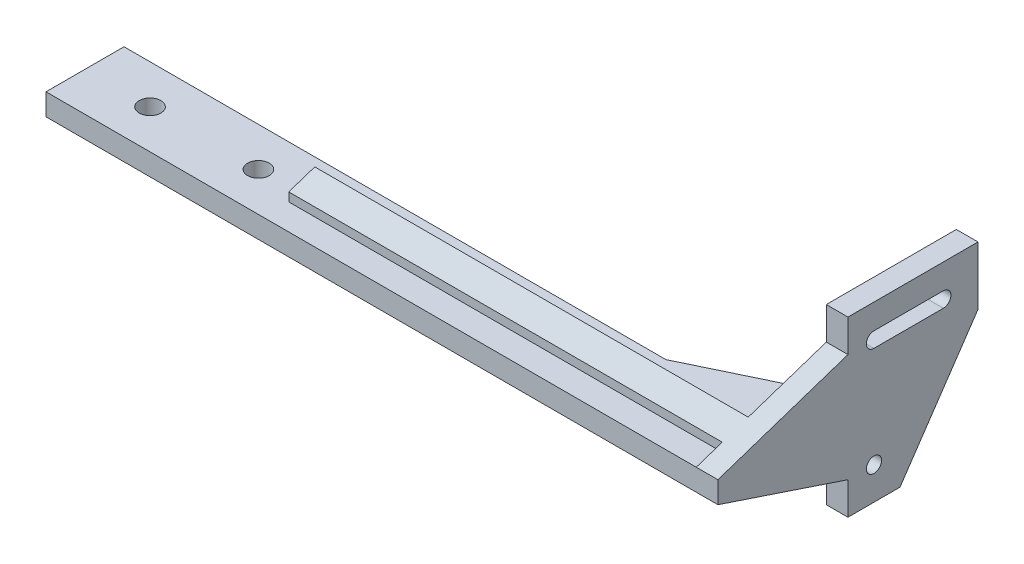
SolidWorks part; units mm, degrees
ref_plane "前视基准面" through (0, 0, 0) normal (0, 0, 1) x (1, 0, 0)
ref_plane "上视基准面" through (0, 0, 0) normal (0, 1, 0) x (1, 0, 0)
ref_plane "右视基准面" through (0, 0, 0) normal (1, 0, 0) x (0, 0, -1)
sketch "草图1" plane through (0, 0, 0) normal (0, 1, 0) x (1, 0, 0)
  line L6 (0, 0) -> (0, -18)
  line L8 (0, -18) -> (150, -18)
  line L9 (150, -18) -> (150, 0)
  line L10 (150, 0) -> (0, 0)
  dimension "D1" = 18
  dimension "D2" = 150
extrude "凸台-拉伸1" add sketch "草图1" along normal blind 5
sketch "草图2" plane through (0, 5, 0) normal (0, 1, 0) x (1, 0, 0)
  line L0 (15, -9) -> (0, -9) construction
  line L1 (0, 0) -> (0, -18) construction
  circle A0 centre (15, -9) radius 2.5
  circle A1 centre (40, -9) radius 2.5
  dimension "D2" = 5
  dimension "D1" = 25
  dimension "D3" = 15
extrude "切除-拉伸1" cut sketch "草图2" against normal through all
sketch "草图6" plane through (150, 0, 0) normal (1, 0, 0) x (0, 0, -1)
  line L0 (12, 15) -> (12, 22.5)
  line L1 (12, 22.5) -> (24, 22.5)
  line L3 (-18, 0) -> (12, -10)
  line L4 (-18, 5) -> (12, 15)
  line L5 (-18, 5) -> (-18, 0)
  line L6 (24, 2.5) -> (-18, 2.5) construction
  line L8 (24, -17.5) -> (42, 9.0298)
  line L9 (24, -17.5) -> (12, -17.5)
  line L10 (12, -17.5) -> (12, -10)
  line L11 (42, 9.0298) -> (42, 22.5)
  line L12 (24, 22.5) -> (42, 22.5)
  point P2 (12, 18.75)
  dimension "D1" = 40
  dimension "D2" = 12
  dimension "D3" = 25
  dimension "D4" = 30
  dimension "D5" = 30
extrude "凸台-拉伸3" add sketch "草图6" along normal blind 5
sketch "草图8" plane through (155, 0, 0) normal (1, 0, 0) x (0, 0, -1)
  line L0 (18, 15) -> (18, -10) construction
  line L1 (18, 2.5) -> (-18, 2.5) construction
  line L3 (12, -17.5) -> (24, -17.5) construction
  line L4 (18, 15) -> (34, 15) construction
  line L7 (18, 16.75) -> (34, 16.75)
  line L8 (18, 13.25) -> (34, 13.25)
  line L9 (-18, 5) -> (-18, 0) construction
  circle A1 centre (18, -10) radius 1.75
  arc A2 (18, 16.75) -> (18, 13.25) centre (18, 15) ccw
  arc A3 (34, 13.25) -> (34, 16.75) centre (34, 15) ccw
  point P12 (18, -17.5)
  point P14 (26, 15)
  dimension "D1" = 3.5
  dimension "D2" = 3.5
  dimension "D3" = 25
  dimension "D4" = 16
extrude "切除-拉伸2" cut sketch "草图8" against normal up to next
sketch "草图10" plane through (150, 0, 0) normal (-1, 0, 0) x (0, 0, 1)
  line L1 (18, 5) -> (0, 5) construction
  line L3 (6, 9) -> (6, 5)
  line L4 (6, 5) -> (9, 5)
  line L6 (12, 7) -> (12, 5)
  line L7 (12, 5) -> (9, 5)
  line L8 (-12, 15) -> (18, 5) construction
  line L9 (6, 9) -> (12, 7)
  dimension "D1" = 6
extrude "凸台-拉伸4" add sketch "草图10" along normal blind 100
sketch "草图11" plane through (0, 5, 0) normal (0, 1, 0) x (1, 0, 0)
  line L0 (150, 0) -> (150, 12)
  line L1 (150, 12) -> (125, 0)
  line L2 (150, 0) -> (0, 0) construction
  line L3 (125, 0) -> (150, 0)
  dimension "D1" = 25
extrude "凸台-拉伸5" add sketch "草图11" against normal up to surface (5 mm away) up to face at (15, 0, 11.5)
